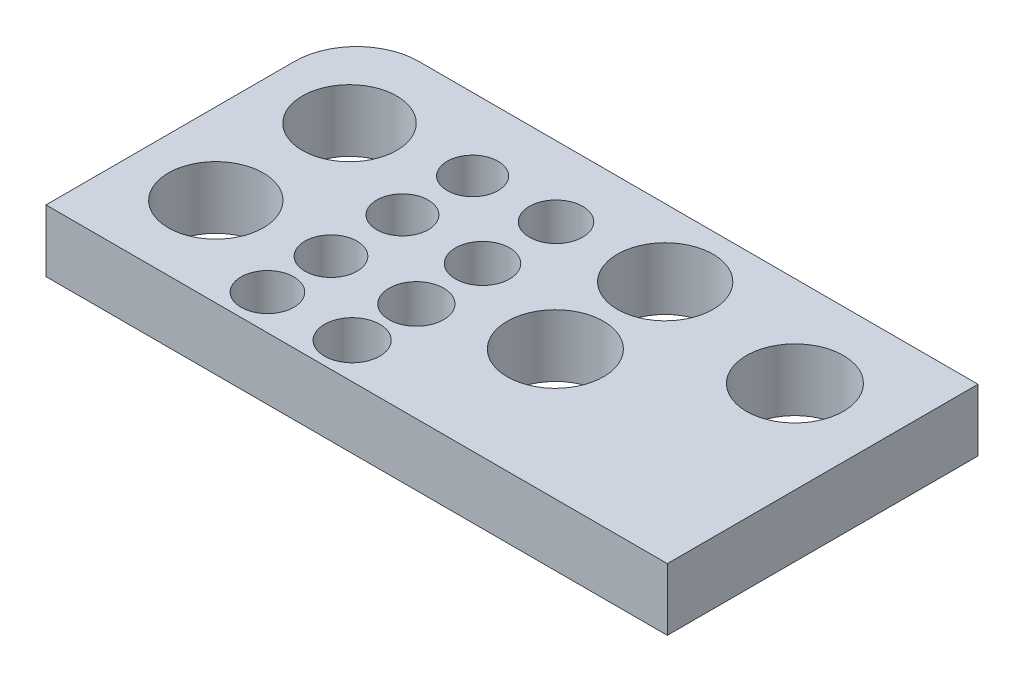
SolidWorks part; units mm, degrees
ref_plane "Front Plane" through (0, 0, 0) normal (0, 0, 1) x (1, 0, 0)
ref_plane "Top Plane" through (0, 0, 0) normal (0, 1, 0) x (1, 0, 0)
ref_plane "Right Plane" through (0, 0, 0) normal (1, 0, 0) x (0, 0, -1)
sketch "Sketch1" plane through (0, 0, 0) normal (0, 1, 0) x (1, 0, 0)
  line L1 (-50, -25) -> (50, -25)
  line L2 (-50, -25) -> (-50, 25)
  line L3 (-50, 25) -> (50, 25)
  line L4 (50, -25) -> (50, 25)
  line L5 (-50, -25) -> (50, 25) construction
  line L6 (-50, 25) -> (50, -25) construction
  point P0 (0, 0)
  dimension "D1" = 100
  dimension "D2" = 50
extrude "Boss-Extrude1" add sketch "Sketch1" along normal blind 10
fillet "Fillet1" radius 10 1 edges at (-50, 5, -25)
hole_wizard "Ø1.0mm Dowel Hole1" positions "Sketch2" profile "Sketch3" hole size "Ø1.0" standard "ANSI Metric" end condition through all
sketch "Sketch2" plane through (0, 10, 0) normal (0, 1, 0) x (1, 0, 0)
  point P0 (-36.9621, 10.8117)
sketch "Sketch3" plane through (-36.9621, 10, -10.8117) normal (1, 0, 0) x (0, 0, 1)
  line L0 (0, 0) -> (0, 10)
  line L1 (0, 10) -> (7.6, 10)
  line L2 (7.6, 10) -> (7.6, 0)
  line L5 (7.6, 0) -> (0, 0)
  line L11 (0, -6.35) -> (0, 107.95) construction
  dimension "Thru Hole Dia." = 15.2
  dimension "Thru Hole Depth" = 10
hole_wizard "Ø1.0mm Dowel Hole2" positions "Sketch4" profile "Sketch5" hole size "Ø1.0" standard "ANSI Metric" end condition through all
sketch "Sketch4" plane through (0, 10, 0) normal (0, 1, 0) x (1, 0, 0)
  point P0 (-36.9621, -10.7052)
  point P4 (-36.9621, -10.7052)
sketch "Sketch5" plane through (-36.9621, 10, 10.7052) normal (1, 0, 0) x (0, 0, 1)
  line L0 (0, 0) -> (0, 10)
  line L1 (0, 10) -> (7.65, 10)
  line L2 (7.65, 10) -> (7.65, 0)
  line L5 (7.65, 0) -> (0, 0)
  line L11 (0, -6.35) -> (0, 107.95) construction
  dimension "Thru Hole Dia." = 15.3
  dimension "Thru Hole Depth" = 10
hole_wizard "Ø1.0mm Dowel Hole3" positions "Sketch6" profile "Sketch7" hole size "Ø1.0" standard "ANSI Metric" end condition through all
sketch "Sketch6" plane through (0, 10, 0) normal (0, 1, 0) x (1, 0, 0)
  point P0 (-19.706, 13.3682)
sketch "Sketch7" plane through (-19.706, 10, -13.3682) normal (1, 0, 0) x (0, 0, 1)
  line L0 (0, 0) -> (0, 10)
  line L1 (0, 10) -> (4.1, 10)
  line L2 (4.1, 10) -> (4.1, 0)
  line L5 (4.1, 0) -> (0, 0)
  line L11 (0, -6.35) -> (0, 107.95) construction
  dimension "Thru Hole Dia." = 8.2
  dimension "Thru Hole Depth" = 10
hole_wizard "Ø1.0mm Dowel Hole4" positions "Sketch8" profile "Sketch9" hole size "Ø1.0" standard "ANSI Metric" end condition through all
sketch "Sketch8" plane through (0, 10, 0) normal (0, 1, 0) x (1, 0, 0)
  point P0 (-19.9191, 2.2902)
sketch "Sketch9" plane through (-19.9191, 10, -2.2902) normal (1, 0, 0) x (0, 0, 1)
  line L0 (0, 0) -> (0, 10)
  line L1 (0, 10) -> (4.15, 10)
  line L2 (4.15, 10) -> (4.15, 0)
  line L5 (4.15, 0) -> (0, 0)
  line L11 (0, -6.35) -> (0, 107.95) construction
  dimension "Thru Hole Dia." = 8.3
  dimension "Thru Hole Depth" = 10
hole_wizard "Ø1.0mm Dowel Hole5" positions "Sketch10" profile "Sketch11" hole size "Ø1.0" standard "ANSI Metric" end condition through all
sketch "Sketch10" plane through (0, 10, 0) normal (0, 1, 0) x (1, 0, 0)
  point P0 (-19.9191, -9.2139)
sketch "Sketch11" plane through (-19.9191, 10, 9.2139) normal (1, 0, 0) x (0, 0, 1)
  line L0 (0, 0) -> (0, 10)
  line L1 (0, 10) -> (4.2, 10)
  line L2 (4.2, 10) -> (4.2, 0)
  line L5 (4.2, 0) -> (0, 0)
  line L11 (0, -6.35) -> (0, 107.95) construction
  dimension "Thru Hole Dia." = 8.4
  dimension "Thru Hole Depth" = 10
hole_wizard "Ø1.0mm Dowel Hole6" positions "Sketch12" profile "Sketch13" hole size "Ø1.0" standard "ANSI Metric" end condition through all
sketch "Sketch12" plane through (0, 10, 0) normal (0, 1, 0) x (1, 0, 0)
  point P0 (-20.0256, -19.3332)
sketch "Sketch13" plane through (-20.0256, 10, 19.3332) normal (1, 0, 0) x (0, 0, 1)
  line L0 (0, 0) -> (0, 10)
  line L1 (0, 10) -> (4.25, 10)
  line L2 (4.25, 10) -> (4.25, 0)
  line L5 (4.25, 0) -> (0, 0)
  line L11 (0, -6.35) -> (0, 107.95) construction
  dimension "Thru Hole Dia." = 8.5
  dimension "Thru Hole Depth" = 10
hole_wizard "Ø1.0mm Dowel Hole7" positions "Sketch14" profile "Sketch15" hole size "Ø1.0" standard "ANSI Metric" end condition through all
sketch "Sketch14" plane through (0, 10, 0) normal (0, 1, 0) x (1, 0, 0)
  point P0 (-6.6042, 13.6877)
sketch "Sketch15" plane through (-6.6042, 10, -13.6877) normal (1, 0, 0) x (0, 0, 1)
  line L0 (0, 0) -> (0, 10)
  line L1 (0, 10) -> (4.3, 10)
  line L2 (4.3, 10) -> (4.3, 0)
  line L5 (4.3, 0) -> (0, 0)
  line L11 (0, -6.35) -> (0, 107.95) construction
  dimension "Thru Hole Dia." = 8.6
  dimension "Thru Hole Depth" = 10
hole_wizard "Ø1.0mm Dowel Hole8" positions "Sketch16" profile "Sketch17" hole size "Ø1.0" standard "ANSI Metric" end condition through all
sketch "Sketch16" plane through (0, 10, 0) normal (0, 1, 0) x (1, 0, 0)
  point P0 (-6.7107, 1.9706)
sketch "Sketch17" plane through (-6.7107, 10, -1.9706) normal (1, 0, 0) x (0, 0, 1)
  line L0 (0, 0) -> (0, 10)
  line L1 (0, 10) -> (4.35, 10)
  line L2 (4.35, 10) -> (4.35, 0)
  line L5 (4.35, 0) -> (0, 0)
  line L11 (0, -6.35) -> (0, 107.95) construction
  dimension "Thru Hole Dia." = 8.7
  dimension "Thru Hole Depth" = 10
hole_wizard "Ø1.0mm Dowel Hole9" positions "Sketch18" profile "Sketch19" hole size "Ø1.0" standard "ANSI Metric" end condition through all
sketch "Sketch18" plane through (0, 10, 0) normal (0, 1, 0) x (1, 0, 0)
  point P0 (-6.3911, -9.0009)
sketch "Sketch19" plane through (-6.3911, 10, 9.0009) normal (1, 0, 0) x (0, 0, 1)
  line L0 (0, 0) -> (0, 10)
  line L1 (0, 10) -> (4.4, 10)
  line L2 (4.4, 10) -> (4.4, 0)
  line L5 (4.4, 0) -> (0, 0)
  line L11 (0, -6.35) -> (0, 107.95) construction
  dimension "Thru Hole Dia." = 8.8
  dimension "Thru Hole Depth" = 10
hole_wizard "Ø1.0mm Dowel Hole10" positions "3DSketch1" profile "Sketch20" hole size "Ø1.0" standard "ANSI Metric" end condition through all
sketch3d "3DSketch1"
  point P0 (-6.4977, 10, 19.2267)
sketch "Sketch20" plane through (-6.4977, 10, 19.2267) normal (1, 0, 0) x (0, 0, 1)
  line L0 (0, 0) -> (0, 10)
  line L1 (0, 10) -> (4.45, 10)
  line L2 (4.45, 10) -> (4.45, 0)
  line L5 (4.45, 0) -> (0, 0)
  line L11 (0, -6.35) -> (0, 107.95) construction
  dimension "Thru Hole Dia." = 8.9
  dimension "Thru Hole Depth" = 10
hole_wizard "Ø1.0mm Dowel Hole11" positions "Sketch21" profile "Sketch22" hole size "Ø1.0" standard "ANSI Metric" end condition through all
sketch "Sketch21" plane through (0, 10, 0) normal (0, 1, 0) x (1, 0, 0)
  point P0 (10.5454, 14.1138)
sketch "Sketch22" plane through (10.5454, 10, -14.1138) normal (1, 0, 0) x (0, 0, 1)
  line L0 (0, 0) -> (0, 10)
  line L1 (0, 10) -> (7.7, 10)
  line L2 (7.7, 10) -> (7.7, 0)
  line L5 (7.7, 0) -> (0, 0)
  line L11 (0, -6.35) -> (0, 107.95) construction
  dimension "Thru Hole Dia." = 15.4
  dimension "Thru Hole Depth" = 10
hole_wizard "Ø1.0mm Dowel Hole12" positions "Sketch23" profile "Sketch24" hole size "Ø1.0" standard "ANSI Metric" end condition through all
sketch "Sketch23" plane through (0, 10, 0) normal (0, 1, 0) x (1, 0, 0)
  point P0 (11.078, -4.101)
sketch "Sketch24" plane through (11.078, 10, 4.101) normal (1, 0, 0) x (0, 0, 1)
  line L0 (0, 0) -> (0, 10)
  line L1 (0, 10) -> (7.75, 10)
  line L2 (7.75, 10) -> (7.75, 0)
  line L5 (7.75, 0) -> (0, 0)
  line L11 (0, -6.35) -> (0, 107.95) construction
  dimension "Thru Hole Dia." = 15.5
  dimension "Thru Hole Depth" = 10
hole_wizard "Ø1.0mm Dowel Hole13" positions "Sketch25" profile "Sketch26" hole size "Ø1.0" standard "ANSI Metric" end condition through all
sketch "Sketch25" plane through (0, 10, 0) normal (0, 1, 0) x (1, 0, 0)
  point P0 (35.1513, 10.3856)
  point P3 (35.1513, 10.3856)
  point P9 (35.1513, 10.3856)
sketch "Sketch26" plane through (35.1513, 10, -10.3856) normal (1, 0, 0) x (0, 0, 1)
  line L0 (0, 0) -> (0, 10)
  line L1 (0, 10) -> (7.8, 10)
  line L2 (7.8, 10) -> (7.8, 0)
  line L5 (7.8, 0) -> (0, 0)
  line L11 (0, -6.35) -> (0, 107.95) construction
  dimension "Thru Hole Dia." = 15.6
  dimension "Thru Hole Depth" = 10
